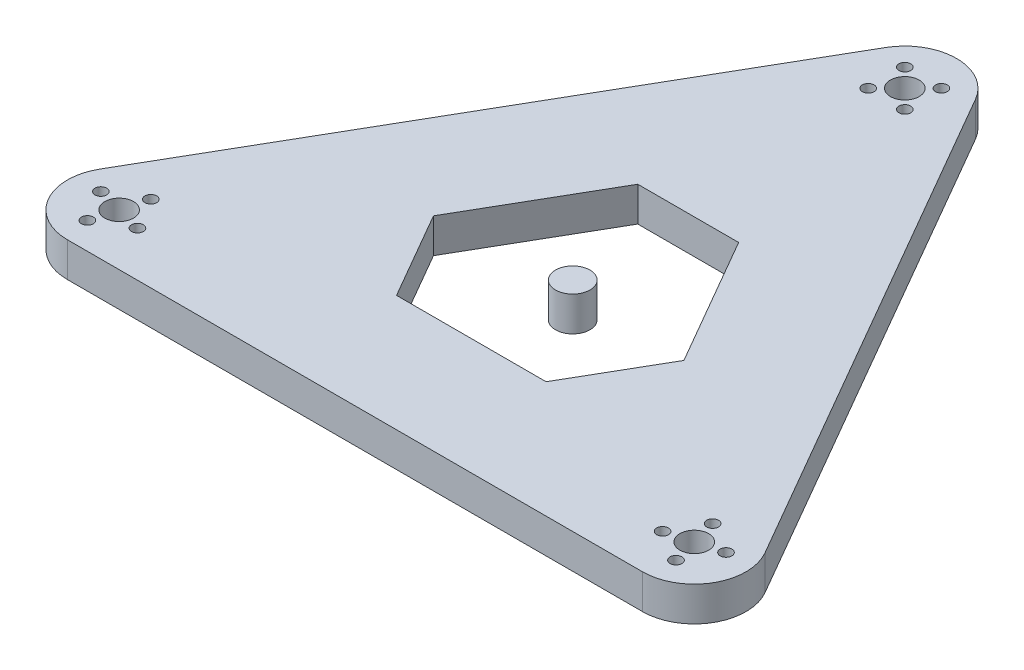
SolidWorks part; units mm, degrees
ref_plane "Front Plane" through (0, 0, 0) normal (0, 0, 1) x (1, 0, 0)
ref_plane "Top Plane" through (0, 0, 0) normal (0, 1, 0) x (1, 0, 0)
ref_plane "Right Plane" through (0, 0, 0) normal (1, 0, 0) x (0, 0, -1)
sketch "Sketch1" plane through (0, 0, 0) normal (0, 1, 0) x (1, 0, 0)
  line L0 (-15.5885, 124.4701) -> (-115.5885, -48.735)
  line L1 (-100, -75.735) -> (100, -75.735)
  line L2 (115.5885, -48.735) -> (15.5885, 124.4701)
  line L3 (0, 115.4701) -> (0, 0) construction
  line L4 (0, 0) -> (-100, -57.735) construction
  line L5 (0, 0) -> (100, -57.735) construction
  line L6 (0, 115.4701) -> (-100, -57.735) construction
  line L7 (-100, -57.735) -> (100, -57.735) construction
  line L8 (100, -57.735) -> (0, 115.4701) construction
  line L18 (0, 0) -> (10.9602, 10.9602) construction
  line L19 (0, 0) -> (-10.9602, -10.9602) construction
  line L20 (0, 0) -> (-10.9602, 10.9602) construction
  line L21 (6.364, 121.834) -> (0, 115.4701) construction
  line L22 (0, 115.4701) -> (-6.364, 109.1061) construction
  line L23 (-6.364, 121.834) -> (0, 115.4701) construction
  line L24 (0, 115.4701) -> (6.364, 109.1061) construction
  line L25 (8.814, 121.834) -> (8.814, 109.1061) construction
  line L27 (-1, 110.5711) -> (-1, 106.5775)
  line L28 (1, 110.5711) -> (1, 106.5775)
  line L29 (97.6706, -49.0417) -> (100, -57.735) construction
  line L30 (100, -57.735) -> (102.3294, -66.4284) construction
  line L31 (91.3067, -60.0644) -> (100, -57.735) construction
  line L32 (100, -57.735) -> (108.6933, -55.4057) construction
  line L33 (98.8956, -46.9199) -> (109.9183, -53.2839) construction
  line L34 (-97.6706, -49.0417) -> (-100, -57.735) construction
  line L35 (-100, -57.735) -> (-102.3294, -66.4284) construction
  line L36 (-108.6933, -55.4057) -> (-100, -57.735) construction
  line L37 (-100, -57.735) -> (-91.3067, -60.0644) construction
  line L38 (-95.5489, -47.8167) -> (-89.1849, -58.8394) construction
  line L39 (0, 0) -> (10.9602, -10.9602) construction
  line L40 (-16.0234, 21.8387) -> (16.0234, 21.8387)
  line L41 (16.0234, 21.8387) -> (21.8387, 16.0234)
  line L42 (21.8387, 16.0234) -> (21.8387, -16.0234)
  line L43 (21.8387, -16.0234) -> (16.0234, -21.8387)
  line L44 (16.0234, -21.8387) -> (-16.0234, -21.8387)
  line L45 (-16.0234, -21.8387) -> (-21.8387, -16.0234)
  line L46 (-21.8387, -16.0234) -> (-21.8387, 16.0234)
  line L47 (-21.8387, 16.0234) -> (-16.0234, 21.8387)
  line L48 (18.9311, 18.9311) -> (-18.9311, -18.9311) construction
  line L49 (-18.9311, 18.9311) -> (18.9311, -18.9311) construction
  line L50 (-17.5362, 40.1528) -> (17.5362, 40.1528)
  line L51 (17.5362, 40.1528) -> (43.5415, -4.8896)
  line L52 (43.5415, -4.8896) -> (26.0053, -35.2632)
  line L53 (26.0053, -35.2632) -> (-26.0053, -35.2632)
  line L54 (-26.0053, -35.2632) -> (-43.5415, -4.8896)
  line L55 (-43.5415, -4.8896) -> (-17.5362, 40.1528)
  circle A1 centre (0, 115.4701) radius 5
  circle A2 centre (100, -57.735) radius 5
  arc A4 (15.5885, 124.4701) -> (-15.5885, 124.4701) centre (0, 115.4701) ccw
  arc A5 (-100, -75.735) -> (-115.5885, -48.735) centre (-100, -57.735) cw
  arc A6 (115.5885, -48.735) -> (100, -75.735) centre (100, -57.735) cw
  circle A7 centre (0, 0) radius 6
  circle A11 centre (-6.364, 121.834) radius 2.45
  circle A12 centre (6.364, 121.834) radius 2.45
  circle A13 centre (-6.364, 109.1061) radius 2.45
  circle A14 centre (6.364, 109.1061) radius 2.45
  arc A15 (-3.7374, 125.4879) -> (-10.0179, 119.2074) centre (-6.364, 121.834) ccw
  arc A16 (10.0179, 119.2074) -> (3.7374, 125.4879) centre (6.364, 121.834) ccw
  arc A17 (3.7374, 105.4522) -> (10.0179, 111.7327) centre (6.364, 109.1061) ccw
  arc A18 (-10.0179, 111.7327) -> (-3.7374, 105.4522) centre (-6.364, 109.1061) ccw
  arc A19 (-10.0179, 119.2074) -> (-10.0179, 111.7327) centre (-15.217, 115.4701) cw
  arc A20 (-3.7374, 125.4879) -> (3.7374, 125.4879) centre (0, 130.6871) ccw
  arc A21 (10.0179, 119.2074) -> (10.0179, 111.7327) centre (15.217, 115.4701) ccw
  arc A22 (3.7374, 105.4522) -> (-3.7374, 105.4522) centre (0, 100.253) ccw
  circle A23 centre (-6.364, 121.834) radius 2.05
  circle A24 centre (-6.364, 109.1061) radius 2.05
  circle A25 centre (6.364, 109.1061) radius 2.05
  circle A26 centre (6.364, 121.834) radius 2.05
  circle A27 centre (100, -57.735) radius 5
  circle A28 centre (-100, -57.735) radius 5
  circle A29 centre (91.3067, -60.0644) radius 2.45
  circle A30 centre (97.6706, -49.0417) radius 2.45
  circle A31 centre (102.3294, -66.4284) radius 2.45
  circle A32 centre (108.6933, -55.4057) radius 2.45
  arc A33 (89.4556, -55.9628) -> (91.7544, -64.5421) centre (91.3067, -60.0644) ccw
  arc A34 (101.7723, -47.1906) -> (93.193, -49.4894) centre (97.6706, -49.0417) ccw
  arc A35 (110.5444, -59.5073) -> (108.2456, -50.928) centre (108.6933, -55.4057) ccw
  arc A36 (98.2277, -68.2794) -> (106.807, -65.9806) centre (102.3294, -66.4284) ccw
  arc A37 (91.7544, -64.5421) -> (98.2277, -68.2794) centre (92.3915, -70.9133) cw
  arc A38 (89.4556, -55.9628) -> (93.193, -49.4894) centre (86.8217, -50.1265) ccw
  arc A39 (101.7723, -47.1906) -> (108.2456, -50.928) centre (107.6085, -44.5567) ccw
  arc A40 (110.5444, -59.5073) -> (106.807, -65.9806) centre (113.1783, -65.3435) ccw
  circle A41 centre (91.3067, -60.0644) radius 2.05
  circle A42 centre (102.3294, -66.4284) radius 2.05
  circle A43 centre (108.6933, -55.4057) radius 2.05
  circle A44 centre (97.6706, -49.0417) radius 2.05
  circle A45 centre (-10.9602, 10.9602) radius 1.55
  circle A46 centre (-108.6933, -55.4057) radius 2.45
  circle A47 centre (-97.6706, -49.0417) radius 2.45
  circle A48 centre (-102.3294, -66.4284) radius 2.45
  circle A49 centre (-91.3067, -60.0644) radius 2.45
  arc A50 (-108.2456, -50.928) -> (-110.5444, -59.5073) centre (-108.6933, -55.4057) ccw
  arc A51 (-93.193, -49.4894) -> (-101.7723, -47.1906) centre (-97.6706, -49.0417) ccw
  arc A52 (-91.7544, -64.5421) -> (-89.4556, -55.9628) centre (-91.3067, -60.0644) ccw
  arc A53 (-106.807, -65.9806) -> (-98.2277, -68.2794) centre (-102.3294, -66.4284) ccw
  arc A54 (-110.5444, -59.5073) -> (-106.807, -65.9806) centre (-113.1783, -65.3435) cw
  arc A55 (-108.2456, -50.928) -> (-101.7723, -47.1906) centre (-107.6085, -44.5567) ccw
  arc A56 (-93.193, -49.4894) -> (-89.4556, -55.9628) centre (-86.8217, -50.1265) ccw
  arc A57 (-91.7544, -64.5421) -> (-98.2277, -68.2794) centre (-92.3915, -70.9133) ccw
  circle A58 centre (-108.6933, -55.4057) radius 2.05
  circle A59 centre (-102.3294, -66.4284) radius 2.05
  circle A60 centre (-91.3067, -60.0644) radius 2.05
  circle A61 centre (-97.6706, -49.0417) radius 2.05
  circle A62 centre (-10.9602, -10.9602) radius 1.55
  circle A63 centre (10.9602, -10.9602) radius 1.55
  circle A64 centre (10.9602, 10.9602) radius 1.55
  point P122 (21.8387, -16.0234)
  point P134 (0, 0)
  point P136 (46.4315, -6.5582)
  point P164 (34.7734, -20.0764)
  point P166 (-34.7734, -20.0764)
  dimension "D1" = 10
  dimension "D3" = 12
  dimension "D4" = 18
  dimension "D7" = 4.9
  dimension "D8" = 4.5
  dimension "D11" = 4.1
  dimension "D12" = 31
  dimension "D6" = 3.1
  dimension "D5" = 200
  dimension "D9" = 9
  dimension "D10" = 2
extrude "Boss-Extrude1" add sketch "Sketch1" along normal blind 12
